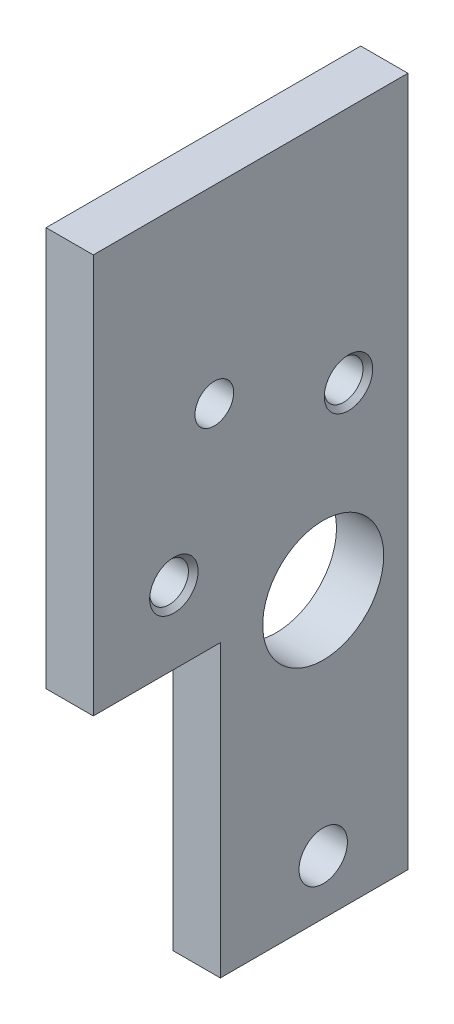
SolidWorks part; units mm, degrees
ref_plane "Front Plane" through (0, 0, 0) normal (0, 0, 1) x (1, 0, 0)
ref_plane "Top Plane" through (0, 0, 0) normal (0, 1, 0) x (1, 0, 0)
ref_plane "Right Plane" through (0, 0, 0) normal (1, 0, 0) x (0, 0, -1)
sketch "Sketch1" plane through (0, 0, 0) normal (1, 0, 0) x (0, 0, -1)
  line L1 (0, 0) -> (-30, 0)
  line L2 (0, 0) -> (0, 57)
  line L3 (0, 57) -> (-30, 57)
  line L4 (-30, 0) -> (-30, 57)
  dimension "D1" = 30
  dimension "D2" = 57
extrude "Boss-Extrude1" add sketch "Sketch1" against normal blind 3.9
sketch "Sketch2" plane through (0, 0, 0) normal (1, 0, 0) x (0, 0, -1)
  line L0 (-30, 0) -> (0, 0) construction
  line L1 (0, 0) -> (0, 57) construction
  circle A0 centre (-7, 23.5) radius 5
  dimension "D1" = 10
  dimension "D2" = 23.5
  dimension "D3" = 7
extrude "Cut-Extrude1" cut sketch "Sketch2" against normal through all
sketch "Sketch4" plane through (0, 0, 0) normal (1, 0, 0) x (0, 0, -1)
  line L0 (0, 0) -> (0, 57) construction
  line L1 (-15.3544, 35.2) -> (-2.5009, 42.379)
  line L2 (-2.5009, 42.379) -> (-15.1448, 49.921)
  line L3 (-15.1448, 49.921) -> (-15.3544, 35.2)
  circle A0 centre (-11, 42.5) radius 4.25 construction
  circle A1 centre (-7, 23.5) radius 5 construction
  dimension "D2" = 19
  dimension "D1" = 8.5
  dimension "D3" = 11
hole_wizard "M4x0.7 Tapped Hole1" [suppressed] positions "3DSketch2" profile "Sketch6" tap size "M4x0.7" standard "ANSI Metric"
sketch3d "3DSketch2"
  point P0 (0, 38.7, 15.3544)
  point P3 (0, 45.879, 2.5009)
  point P6 (0, 53.421, 15.1448)
sketch "Sketch6" plane through (0, 38.7, 15.3544) normal (0, 1, 0) x (0, 0, -1)
  line L0 (0, 0) -> (0, 4)
  line L1 (0, 4) -> (1.05, 4)
  line L3 (1.05, 4) -> (1.05, 2)
  line L4 (1.05, 2) -> (1.65, 2)
  line L5 (1.65, 2) -> (1.65, 0)
  line L7 (1.65, 0) -> (0, 0)
  line L11 (0, -6.35) -> (0, 107.95) construction
  dimension "Thru Tap Drill Dia." = 2.1
  dimension "Thru Tap Drill Depth" = 4
  dimension "Thread Major Dia." = 3.3
  dimension "Thread Depth" = 2
sketch "Sketch7" [suppressed] plane through (-4, 0, 0) normal (-1, 0, 0) x (0, 0, 1)
  line L1 (15.3544, 38.7) -> (15.1448, 53.421)
  line L2 (15.1448, 53.421) -> (2.5009, 45.879)
  line L3 (2.5009, 45.879) -> (15.3544, 38.7)
  circle A0 centre (11, 46) radius 4.25 construction
hole_wizard "CBORE for M3 Pan Head Machine Screw1" [suppressed] positions "3DSketch3" profile "Sketch8" counterbore size "M3" standard "ANSI Metric"
sketch3d "3DSketch3" [suppressed]
  point P0 (-4, 46, 11)
sketch "Sketch8" [suppressed] plane through (-4, 46, 11) normal (0, 1, 0) x (0, 0, 1)
  line L0 (0, 0) -> (0, 4)
  line L1 (0, 4) -> (1.6, 4)
  line L3 (1.6, 4) -> (1.6, 1)
  line L4 (1.6, 1) -> (5.1, 1)
  line L5 (5.1, 1) -> (5.1, 0)
  line L7 (5.1, 0) -> (0, 0)
  line L11 (0, -6.35) -> (0, 107.95) construction
  dimension "Thru Hole Dia." = 3.2
  dimension "Thru Hole Depth" = 4
  dimension "C'Bore Dia." = 10.2
  dimension "C'Bore Depth" = 1
sketch "Sketch10" plane through (0, 0, 0) normal (1, 0, 0) x (0, 0, -1)
  line L0 (0, 0) -> (0, 57) construction
  line L1 (-30, 0) -> (0, 0) construction
  circle A0 centre (-7, 4.5) radius 2
  dimension "D1" = 4
  dimension "D2" = 7
  dimension "D3" = 4.5
hole_wizard "Ø4.0 (4) Diameter Hole1" positions "3DSketch4" profile "Sketch11" hole size "Ø4.0" standard "ANSI Metric" end condition through all
sketch3d "3DSketch4"
  point P0 (0, 4.5, 7)
sketch "Sketch11" plane through (0, 4.5, 7) normal (0, 1, 0) x (0, 0, -1)
  line L0 (0, 0) -> (0, 3.9)
  line L1 (0, 3.9) -> (2, 3.9)
  line L2 (2, 3.9) -> (2, 0)
  line L5 (2, 0) -> (0, 0)
  line L11 (0, -6.35) -> (0, 107.95) construction
  dimension "Thru Hole Dia." = 4
  dimension "Thru Hole Depth" = 3.9
sketch "Sketch12" plane through (0, 0, 0) normal (1, 0, 0) x (0, 0, -1)
  line L1 (-30, 0) -> (-15.5, 0)
  line L2 (-30, 0) -> (-30, 24)
  line L3 (-30, 24) -> (-15.5, 24)
  line L4 (-15.5, 0) -> (-15.5, 24)
  dimension "D1" = 14.5
  dimension "D2" = 24
extrude "Cut-Extrude2" cut sketch "Sketch12" against normal through all
sketch "Sketch13" plane through (-3.9, 0, 0) normal (-1, 0, 0) x (0, 0, 1)
  line L0 (0, 0) -> (0, 57) construction
  circle A0 centre (16, 41.3606) radius 1.5
  circle A1 centre (7, 23.5) radius 5 construction
  dimension "D1" = 3
  dimension "D2" = 20
  dimension "D3" = 16
hole_wizard "CBORE for M3 Pan Head Machine Screw2" positions "3DSketch5" profile "Sketch14" counterbore size "M3" standard "ANSI Metric" end condition through all
sketch3d "3DSketch5"
  point P0 (-3.9, 41.3606, 16)
sketch "Sketch14" plane through (-3.9, 41.3606, 16) normal (0, 1, 0) x (0, 0, 1)
  line L0 (0, 0) -> (0, 3.9)
  line L1 (0, 3.9) -> (1.6, 3.9)
  line L3 (1.6, 3.9) -> (1.6, 1)
  line L4 (1.6, 1) -> (4.5, 1)
  line L5 (4.5, 1) -> (4.5, 0)
  line L7 (4.5, 0) -> (0, 0)
  line L11 (0, -6.35) -> (0, 107.95) construction
  dimension "Thru Hole Dia." = 3.2
  dimension "Thru Hole Depth" = 3.9
  dimension "C'Bore Dia." = 9
  dimension "C'Bore Depth" = 1
sketch "Sketch16" plane through (0, 0, 0) normal (1, 0, 0) x (0, 0, -1)
  line L0 (-16, 41.3606) -> (-7, 23.5) construction
  circle A0 centre (-19.3397, 30.0326) radius 1.5
  circle A1 centre (-16, 41.3606) radius 1.6 construction
  circle A2 centre (-4.9083, 37.3046) radius 1.5
  dimension "D1" = 3
  dimension "D2" = 8.08
  dimension "D3" = 11.81
hole_wizard "CSK for M3 Flat Head Machine Screw1" positions "3DSketch7" profile "Sketch18" countersink size "M3" standard "ANSI Metric" end condition through all
sketch3d "3DSketch7"
  point P0 (0, 30.0326, 19.3397)
  point P3 (0, 37.3046, 4.9083)
sketch "Sketch18" plane through (0, 30.0326, 19.3397) normal (0, 1, 0) x (0, 0, -1)
  line L0 (0, 0) -> (0, 3.9)
  line L1 (0, 3.9) -> (1.6, 3.9)
  line L2 (1.6, 3.9) -> (1.6, 0.4)
  line L3 (1.6, 0.4) -> (2, 0)
  line L5 (2, 0) -> (0, 0)
  line L6 (-1.6, 0.4) -> (-2, 0) construction
  line L11 (0, -6.35) -> (0, 107.95) construction
  dimension "Thru Hole Dia." = 3.2
  dimension "Thru Hole Depth" = 3.9
  dimension "Near C'Sink Dia." = 4
  dimension "Near C'Sink Angle" = 90
sketch "Sketch19" plane through (-3.9, 0, 0) normal (-1, 0, 0) x (0, 0, 1)
  line L0 (30, 24) -> (30, 57)
  line L1 (30, 24) -> (26, 24)
  line L2 (30, 57) -> (26, 57)
  line L3 (26, 24) -> (26, 57)
  dimension "D1" = 4
extrude "Cut-Extrude3" cut sketch "Sketch19" against normal through all
